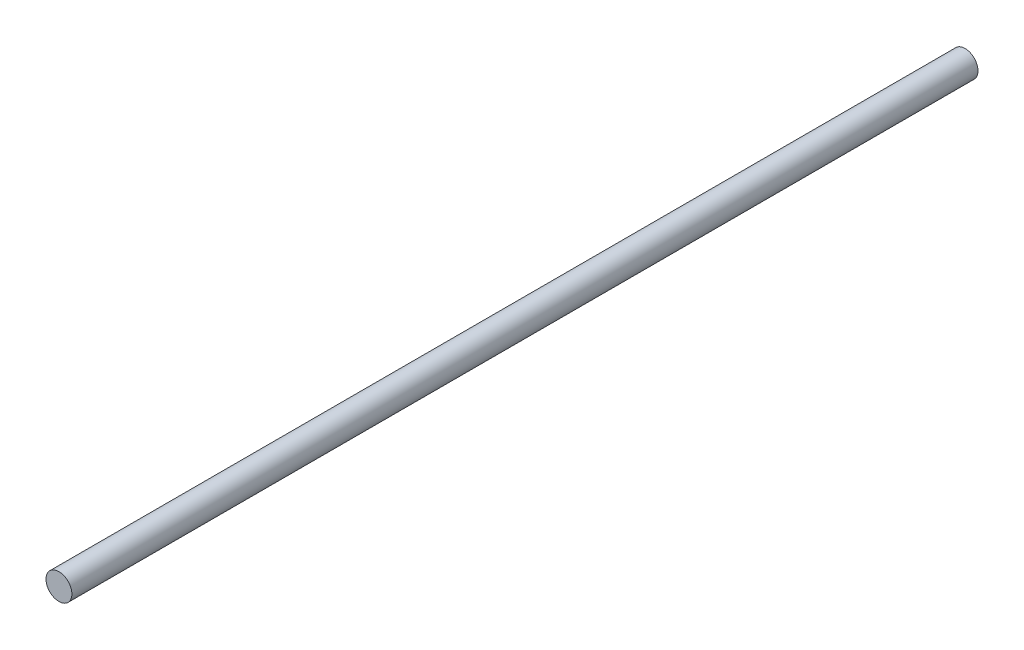
SolidWorks part; units mm, degrees
ref_plane "Front" through (0, 0, 0) normal (0, 0, 1) x (1, 0, 0)
ref_plane "Top" through (0, 0, 0) normal (0, 1, 0) x (1, 0, 0)
ref_plane "Right" through (0, 0, 0) normal (1, 0, 0) x (0, 0, -1)
sketch "Esquisse1" plane through (0, 0, 0) normal (0, 0, 1) x (1, 0, 0)
  circle A0 centre (0, 0) radius 8
  dimension "D1" = 16
extrude "Boss.-Extru.1" add sketch "Esquisse1" along normal blind 560
